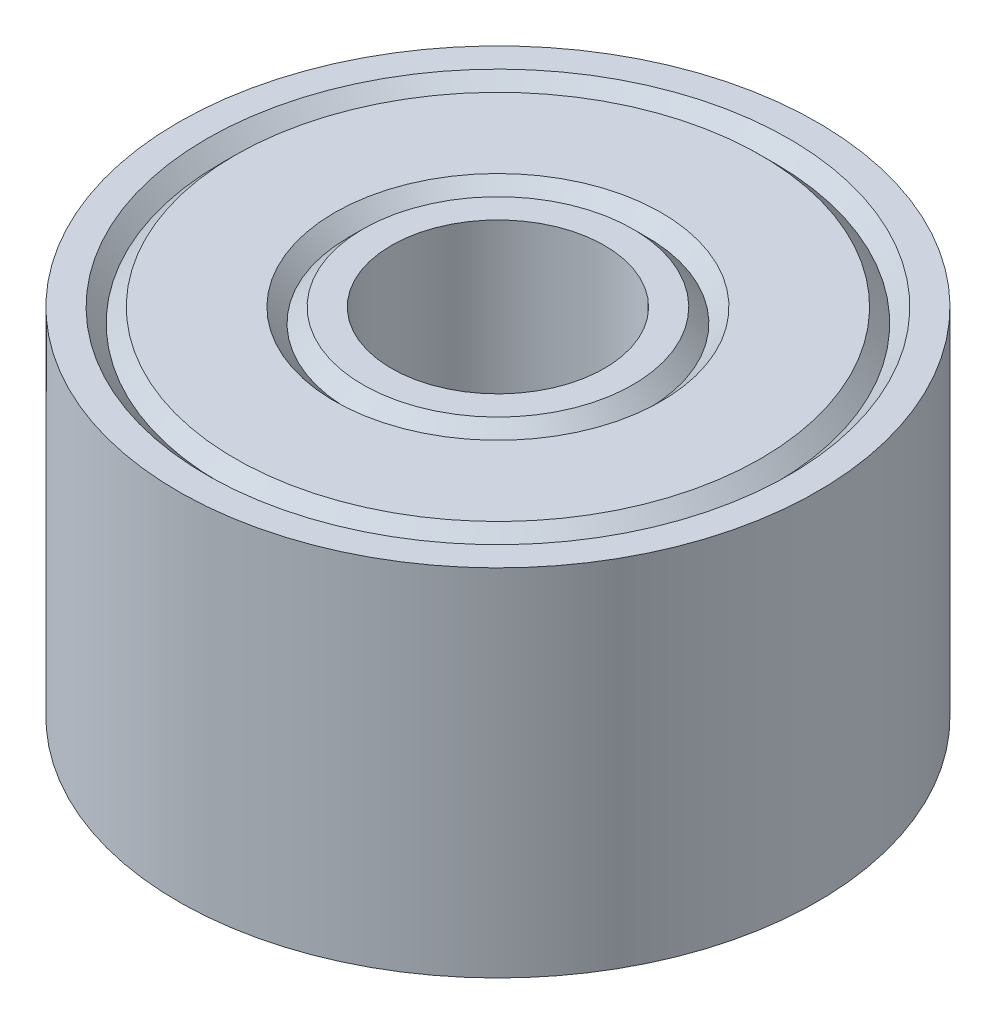
SolidWorks part; units mm, degrees
ref_plane "Front Plane" through (0, 0, 0) normal (0, 0, 1) x (1, 0, 0)
ref_plane "Top Plane" through (0, 0, 0) normal (0, 1, 0) x (1, 0, 0)
ref_plane "Right Plane" through (0, 0, 0) normal (1, 0, 0) x (0, 0, -1)
sketch "Sketch1" plane through (0, 0, 0) normal (0, 0, 1) x (1, 0, 0)
  line L0 (0, 2.5) -> (0, -2.5) construction
  line L1 (-1.5, 2.5) -> (-1.9, 2.5)
  line L2 (-1.5, 2.5) -> (-1.5, -2.5)
  line L3 (-1.5, -2.5) -> (-1.9, -2.5)
  line L4 (-4.5, 2.5) -> (-4.5, -2.5)
  line L5 (-4.1, 2.5) -> (-3.9, 2.3)
  line L6 (-3.9, 2.3) -> (-3.7, 2.5)
  line L7 (-2.3, 2.5) -> (-2.1, 2.3)
  line L8 (-2.1, 2.3) -> (-1.9, 2.5)
  line L9 (-4.1, -2.5) -> (-3.9, -2.3)
  line L10 (-3.9, -2.3) -> (-3.7, -2.5)
  line L11 (-2.3, -2.5) -> (-2.1, -2.3)
  line L12 (-2.1, -2.3) -> (-1.9, -2.5)
  line L13 (-2.3, -2.5) -> (-3.7, -2.5)
  line L14 (-4.1, -2.5) -> (-4.5, -2.5)
  line L15 (-4.1, 2.5) -> (-4.5, 2.5)
  line L16 (-2.3, 2.5) -> (-3.7, 2.5)
  line L17 (-3.9, 2.3) -> (-2.1, 2.3) construction
  line L18 (-3.9, 2.3) -> (-3.9, -2.3) construction
  line L19 (-2.1, -2.3) -> (-3.9, -2.3) construction
  line L20 (-2.1, 2.3) -> (-2.1, -2.3) construction
  line L21 (-3.9, 0) -> (-3.3, 0) construction
  line L22 (-1.9, 2.5) -> (-2.3, 2.5) construction
  line L23 (-3.3, 0) -> (-2.7, 0) construction
  line L24 (-3.9, 0) -> (-4.5, 0) construction
  line L25 (-2.7, 0) -> (-2.1, 0) construction
  line L26 (-2.1, 0) -> (-1.5, 0) construction
  dimension "D1" = 5
  dimension "D2" = 3
  dimension "D3" = 9
revolve "Revolve1" add sketch "Sketch1" angle 360 about L0
